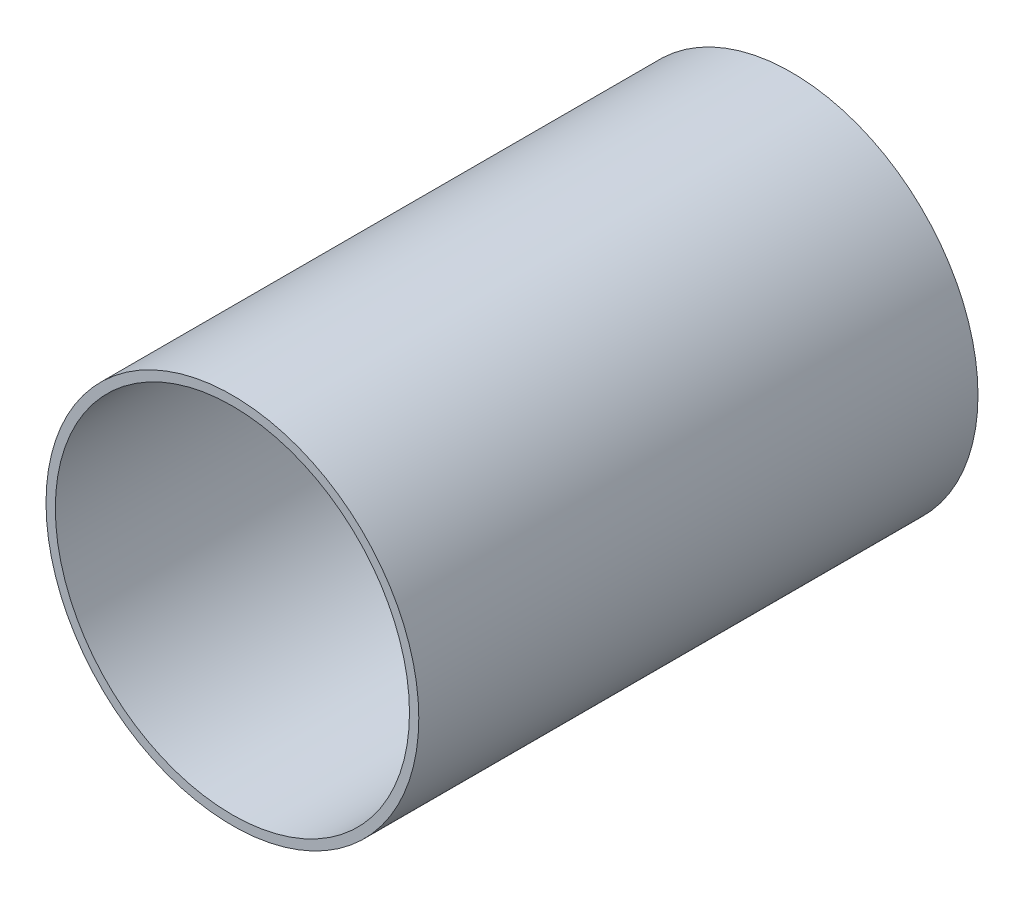
SolidWorks part; units mm, degrees
material "Thornel Mat VMA"
ref_plane "前视基准面" through (0, 0, 0) normal (0, 0, 1) x (1, 0, 0)
ref_plane "上视基准面" through (0, 0, 0) normal (0, 1, 0) x (1, 0, 0)
ref_plane "右视基准面" through (0, 0, 0) normal (1, 0, 0) x (0, 0, -1)
sketch "草图1" plane through (0, 0, 0) normal (0, 0, 1) x (1, 0, 0)
  circle A0 centre (0, 0) radius 9.5
  circle A1 centre (0, 0) radius 10
  dimension "D1" = 19
  dimension "D2" = 20
extrude "凸台-拉伸1" add sketch "草图1" along normal blind 30
